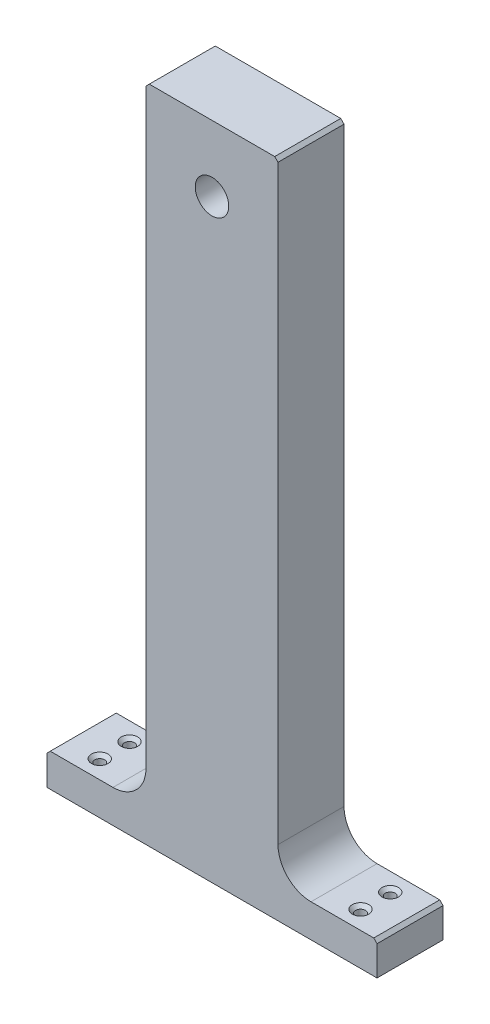
SolidWorks part; units mm, degrees
ref_plane "Front Plane" through (0, 0, 0) normal (0, 0, 1) x (1, 0, 0)
ref_plane "Top Plane" through (0, 0, 0) normal (0, 1, 0) x (1, 0, 0)
ref_plane "Right Plane" through (0, 0, 0) normal (1, 0, 0) x (0, 0, -1)
sketch "Sketch1" plane through (0, 0, 0) normal (0, 0, 1) x (1, 0, 0)
  line L0 (143.7604, 196.4301) -> (158.6854, 196.4301) construction
  line L1 (138.6854, 16.4301) -> (158.6854, 16.4301)
  line L2 (138.6854, 16.4301) -> (138.6854, 191.3551)
  line L3 (138.6854, 216.4301) -> (158.6854, 216.4301)
  line L4 (158.6854, 26.4301) -> (158.6854, 216.4301)
  line L5 (158.6854, 16.4301) -> (188.6854, 16.4301)
  line L7 (158.6854, 26.4301) -> (188.6854, 26.4301)
  line L8 (188.6854, 16.4301) -> (188.6854, 26.4301)
  line L9 (138.6854, 201.5051) -> (138.6854, 216.4301)
  arc A0 (138.6854, 191.3551) -> (138.6854, 201.5051) centre (138.6854, 196.4301) ccw
  dimension "D1" = 200
  dimension "D2" = 20
  dimension "D3" = 30
  dimension "D4" = 10
  dimension "D5" = 20
extrude "Boss-Extrude2" add sketch "Sketch1" along normal blind 20
fillet "Fillet1" radius 10 1 edges at (158.6854, 26.4301, 10)
chamfer "Chamfer1" distance 1 angle 45 2 edges at (188.6854, 26.4301, 10) (158.6854, 216.4301, 10)
sketch "Sketch2" plane through (0, 26.4301, 0) normal (0, 1, 0) x (1, 0, 0)
  line L0 (178.1854, 0) -> (178.1854, -20) construction
  line L1 (187.6854, 0) -> (168.6854, 0) construction
  line L2 (187.6854, -20) -> (168.6854, -20) construction
  line L4 (187.6854, -20) -> (187.6854, 0) construction
  line L5 (168.6854, 0) -> (168.6854, -20) construction
  line L6 (168.6854, -5.5) -> (187.6854, -5.5) construction
  line L7 (168.6854, -14.5) -> (187.6854, -14.5) construction
  circle A0 centre (178.1854, -5.5) radius 1.5
  circle A1 centre (178.1854, -14.5) radius 1.5
  dimension "D1" = 5.5
  dimension "D2" = 5.5
extrude "Cut-Extrude1" cut sketch "Sketch2" against normal blind 20
chamfer "Chamfer3" distance 1 angle 45 2 edges at (178.1854, 26.4301, 16) (178.1854, 26.4301, 7)
mirror "Mirror1" about plane through (138.6854, 16.4301, 20) normal (1, 0, 0) of bodies 103
